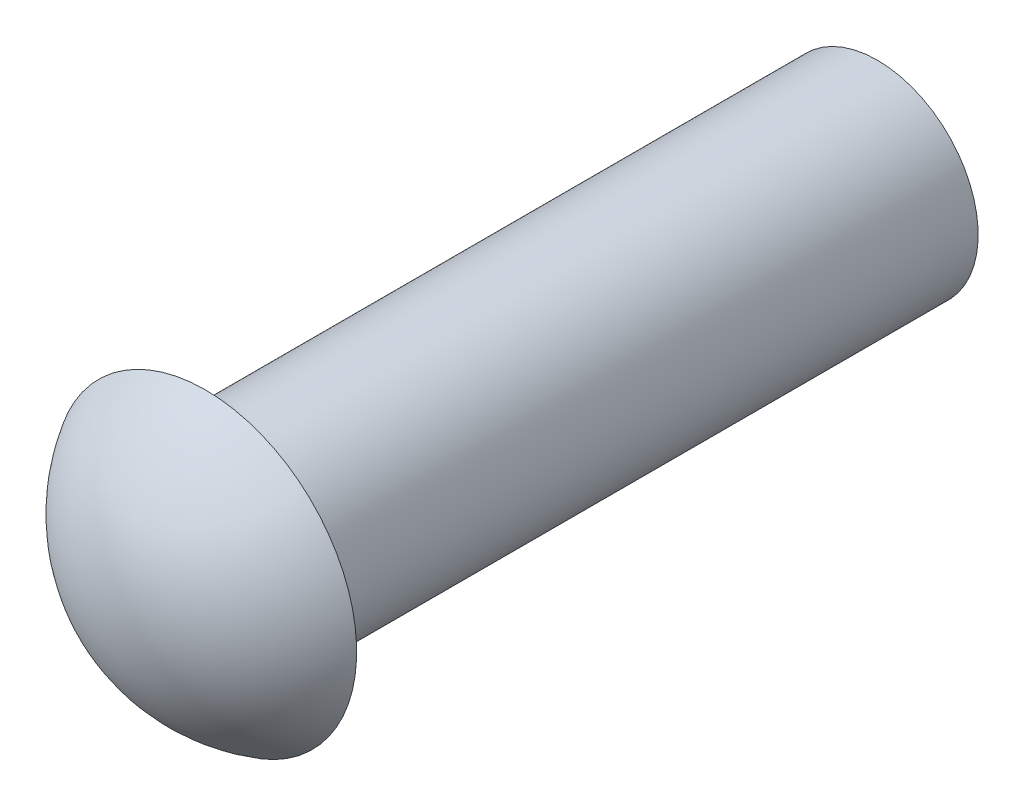
SolidWorks part; units mm, degrees
ref_plane "Front Plane" through (0, 0, 0) normal (1, 0, 0) x (0, 1, 0)
ref_plane "Top Plane" through (0, 0, 0) normal (0, 0, 1) x (0, 1, 0)
ref_plane "Right Plane" through (0, 0, 0) normal (0, 1, 0) x (-1, 0, 0)
sketch "Sketch1" plane through (0, 0, 0) normal (1, 0, 0) x (0, 1, 0)
  line L0 (-3, 20) -> (1.5, 20)
  line L1 (0, 0) -> (-3, 0)
  line L2 (0, 0) -> (0, 20)
  line L3 (0, 20) -> (-3, 20)
  line L4 (-3, 0) -> (-3, 20)
  line L5 (-3, 22.5981) -> (-3, 17.4019) construction
  line L6 (-1.5, 20) -> (-1.5, 0) construction
  line L7 (-3, 17.4019) -> (1.5, 20) construction
  line L8 (-3, 22.5981) -> (-3, 20)
  arc A0 (1.5, 20) -> (-3, 22.5981) centre (-3, 17.4019) ccw
  dimension "D1" = 3
  dimension "D2" = 20
  dimension "D3" = 60
  dimension "D4" = 4.5
revolve "Revolve2" add sketch "Sketch1" angle 360 about L4
equation "\"D1@Sketch1\"=3mm"
equation "\"D2@Sketch1\"=20mm"
equation "\"D4@Sketch1\"=4.5mm"
